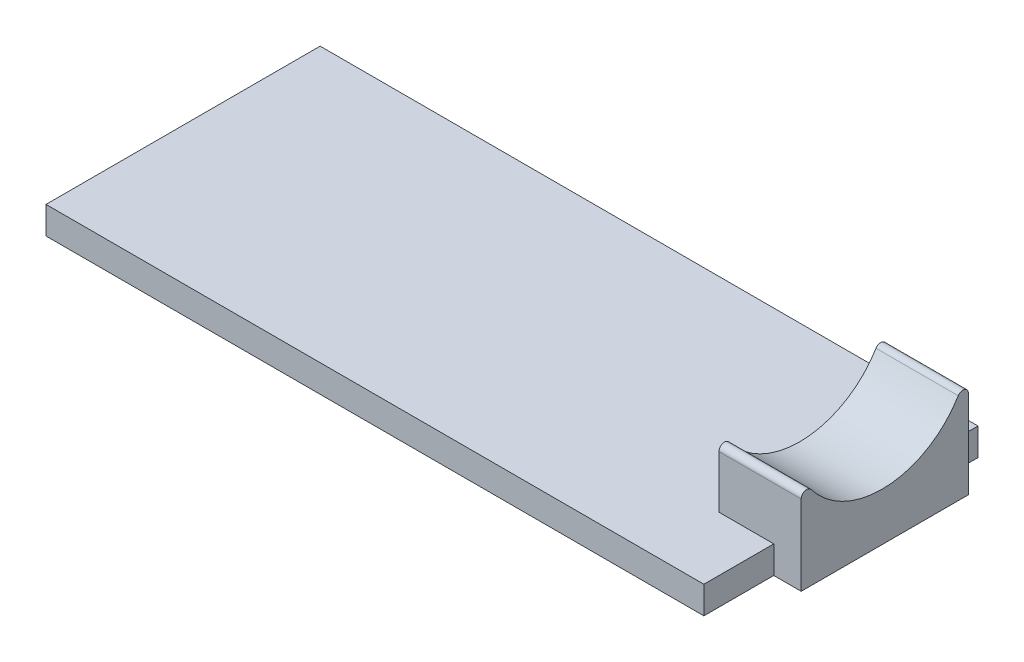
SolidWorks part; units mm, degrees
ref_plane "Front Plane" through (0, 0, 0) normal (0, 0, 1) x (1, 0, 0)
ref_plane "Top Plane" through (0, 0, 0) normal (0, 1, 0) x (1, 0, 0)
ref_plane "Right Plane" through (0, 0, 0) normal (1, 0, 0) x (0, 0, -1)
sketch "Sketch1" plane through (0, 0, 0) normal (0, 1, 0) x (1, 0, 0)
  line L1 (0, 0) -> (-24, 0)
  line L2 (0, 0) -> (0, 10)
  line L3 (0, 10) -> (-24, 10)
  line L4 (-24, 0) -> (-24, 10)
  dimension "D1" = 24
  dimension "D2" = 10
extrude "Boss-Extrude1" add sketch "Sketch1" along normal blind 1
sketch "Sketch2" plane through (0, 1, 0) normal (0, 1, 0) x (1, 0, 0)
  line L0 (-1.5, 0) -> (-1.5, 1.2) construction
  line L2 (1, 2.55) -> (-2, 2.55)
  line L3 (-2, 2.55) -> (-2, 8.65)
  line L4 (-2, 8.65) -> (1, 8.65)
  line L5 (1, 8.65) -> (1, 2.55)
  line L6 (-24, 0) -> (0, 0) construction
  line L7 (0, 10) -> (0, 8.65) construction
  line L8 (-1.5, 1.2) -> (0, 1.2) construction
  line L9 (0, 0) -> (0, 10) construction
  line L10 (0, 1.2) -> (0, 2.55) construction
  dimension "D1" = 1.2
  dimension "D2" = 6.1
  dimension "D3" = 3
  dimension "D4" = 1
extrude "Boss-Extrude2" add sketch "Sketch2" along normal blind 3.25
sketch "Sketch3" plane through (-2, 0, 0) normal (1, 0, 0) x (0, 0, -1)
  line L0 (2.25, 5) -> (8.75, 5) construction
  circle A0 centre (5.5, 5) radius 3.25
  dimension "D1" = 6.5
extrude "Cut-Extrude1" cut sketch "Sketch3" along normal up to surface (3 mm away) up to face at (1, 2.625, -5.6)
fillet "Fillet1" radius 0.2 2 edges at (-0.5, 4.2, -8.65) (-0.5, 3.6362, -2.55)
sketch "Sketch4" plane through (0, 1, 0) normal (0, -1, 0) x (1, 0, 0)
  line L1 (0, -2.55) -> (1, -2.55)
  line L2 (0, -2.55) -> (0, -8.65)
  line L3 (0, -8.65) -> (1, -8.65)
  line L4 (1, -2.55) -> (1, -8.65)
extrude "Boss-Extrude3" add sketch "Sketch4" along normal up to surface (1 mm away) up to face at (-12, 0, -5)
